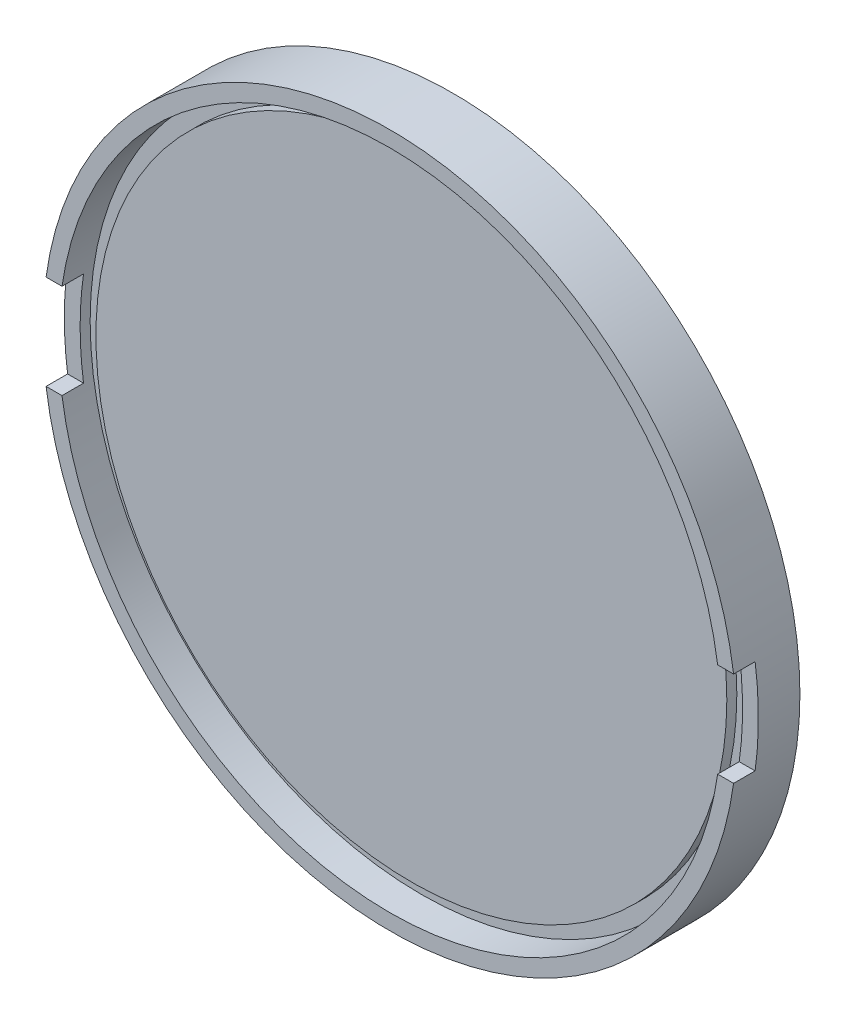
SolidWorks part; units mm, degrees
other "Plate Border" parameters "D1"=65.0383, "D2"=5, "D3"=10
material "PLA"
ref_plane "Front Plane" through (0, 0, 0) normal (1, 0, 0) x (0, 1, 0)
ref_plane "Top Plane" through (0, 0, 0) normal (0, 0, 1) x (0, 1, 0)
ref_plane "Right Plane" through (0, 0, 0) normal (0, 1, 0) x (-1, 0, 0)
sketch "Sketch2" plane through (0, 0, 0) normal (0, 0, 1) x (0, 1, 0)
  circle A0 centre (0, 0) radius 100
  circle A1 centre (0, 0) radius 105
  circle A2 centre (0, 0) radius 110
  dimension "D1" = 200
extrude "Base Plate" add sketch "Sketch2" along normal blind 3.175 contours A0
sketch "Sketch3" plane through (0, 0, 0) normal (0, 0, -1) x (1, 0, 0)
  circle A1 centre (0, 0) radius 110
  circle A2 centre (0, 0) radius 105
  circle A3 centre (0, 0) radius 105
  dimension "D1" = 5
  dimension "D2" = 5
extrude "Boss-Extrude2" add sketch "Sketch3" against normal blind 10 separate body
sketch "Sketch10" plane through (0, 0, 0) normal (0, 0, -1) x (1, 0, 0)
  circle A0 centre (0, 0) radius 110
  circle A1 centre (0, 0) radius 110 construction
extrude "Boss-Extrude4" add sketch "Sketch10" along normal blind 10
sketch "Sketch12" plane through (0, 0, 0) normal (1, 0, 0) x (0, 1, 0)
  line L0 (-110, -10) -> (110, -10) construction
  line L1 (110, -10) -> (110, 10) construction
  line L2 (110, 10) -> (-110, 10) construction
  line L3 (-110, 10) -> (-110, -10) construction
  line L4 (-110, -10) -> (110, -10)
  line L5 (110, -10) -> (110, 10)
  line L6 (110, 10) -> (-110, 10)
  line L7 (-110, 10) -> (-110, -10)
  line L8 (100, 3.175) -> (-100, 3.175) construction
  line L9 (-15, 3.175) -> (15, 3.175)
  line L10 (-15, 3.175) -> (-15, 10)
  line L11 (-15, 10) -> (15, 10)
  line L12 (15, 3.175) -> (15, 10)
  line L13 (-15, 3.175) -> (15, 10) construction
  line L14 (-15, 10) -> (15, 3.175) construction
  line L15 (100, 3.175) -> (-100, 3.175)
  point P2 (0, 6.5875)
  point P9 (0, 0)
  dimension "D1" = 30
extrude "Cut-Extrude2" cut sketch "Sketch12" against normal through all and the other way through all contours L10 L9 L12 L11
equation "\"plateDiameter\"= 200'Diameter of the Aluminum plate"
equation "\"D1@Sketch2\"=\"plateDiameter\""
equation "\"border_cut_width\"= 30"
